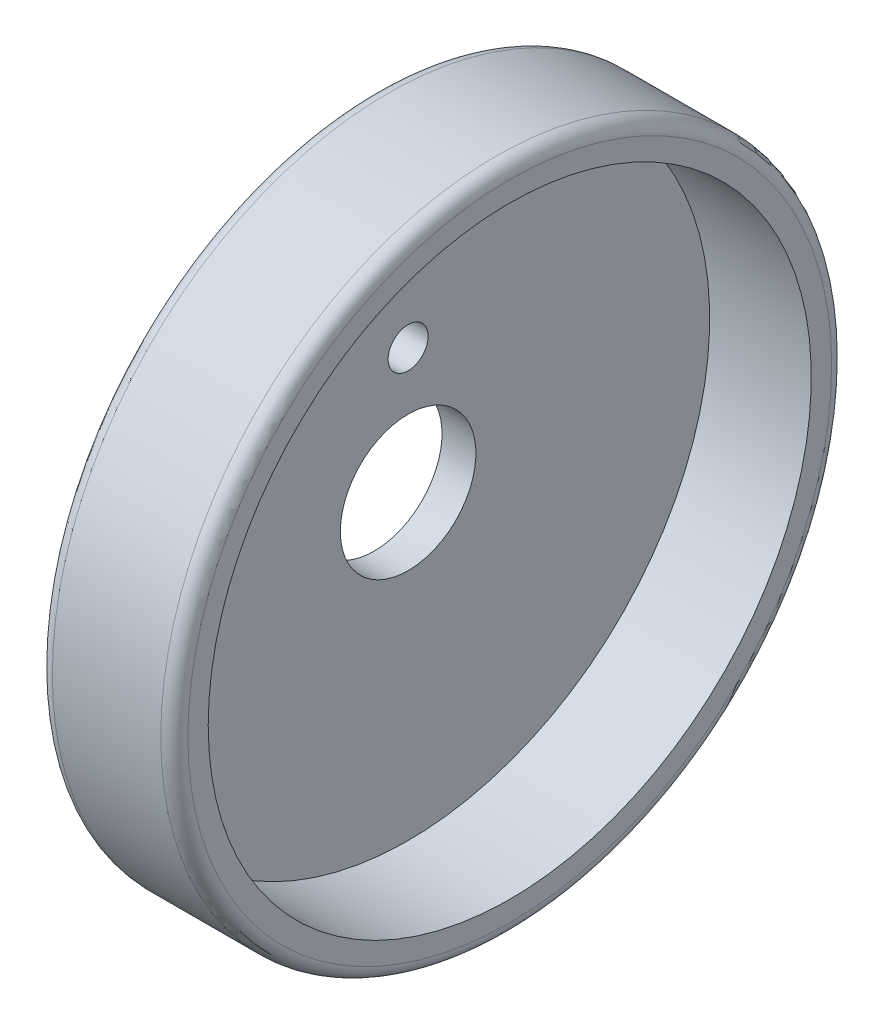
SolidWorks part; units mm, degrees
ref_plane "Front Plane" through (0, 0, 0) normal (0, 0, 1) x (1, 0, 0)
ref_plane "Top Plane" through (0, 0, 0) normal (0, 1, 0) x (1, 0, 0)
ref_plane "Right Plane" through (0, 0, 0) normal (1, 0, 0) x (0, 0, -1)
sketch "Sketch1" plane through (0, 0, 0) normal (0, 0, 1) x (1, 0, 0)
  line L0 (-12.3095, 14.7222) -> (-27.3095, 14.7222)
  line L1 (-27.3095, 14.7222) -> (-27.3095, -19.7778)
  line L2 (-27.3095, -19.7778) -> (-32.3095, -19.7778)
  line L3 (-32.3095, -19.7778) -> (-32.3095, 19.7222)
  line L4 (-32.3095, 19.7222) -> (-12.3095, 19.7222)
  line L5 (-12.3095, 19.7222) -> (-12.3095, 14.7222)
  line L6 (-53.2788, -29.7778) -> (-4.0897, -29.7778) construction
  dimension "D1" = 5
  dimension "D2" = 5
  dimension "D3" = 15
  dimension "D4" = 34.5
  dimension "D5" = 10
  dimension "D6" = 44.5
revolve "Revolve1" add sketch "Sketch1" angle 360 about L6
fillet "Fillet2" radius 2 1 edges at (-32.3095, -29.7778, 49.5)
fillet "Fillet3" radius 2 1 edges at (-12.3095, -29.7778, 49.5)
ref_plane "Plane1" through (-27.3095, 0, 0) normal (1, 0, 0) x (0, 0, -1)
sketch "Sketch2" plane through (-27.3095, 0, 0) normal (1, 0, 0) x (0, 0, -1)
  line L0 (0, -29.7778) -> (56.4685, -29.7778) construction
  line L1 (0, -29.7778) -> (-56.075, -29.7778) construction
  line L2 (0, 61.4609) -> (0, -84.0164) construction
  line L3 (-23.1642, -11.2778) -> (23.1642, -11.2778) construction
  line L4 (0, -19.7778) -> (59.6647, -19.7778) construction
  line L5 (-21.2045, -2.7778) -> (54.9615, -2.7778) construction
  circle A0 centre (0, -11.2778) radius 2.95
  circle A2 centre (0, -29.7778) radius 10 construction
  point P11 (0, -11.2778)
  point P12 (0, -11.2778)
  dimension "D5" = 5.9
  dimension "D1" = 17
  dimension "D2" = 8.5
  dimension "D3" = 8.5
  dimension "D4" = 27
extrude "Cut-Extrude1" cut sketch "Sketch2" against normal mid plane 26
